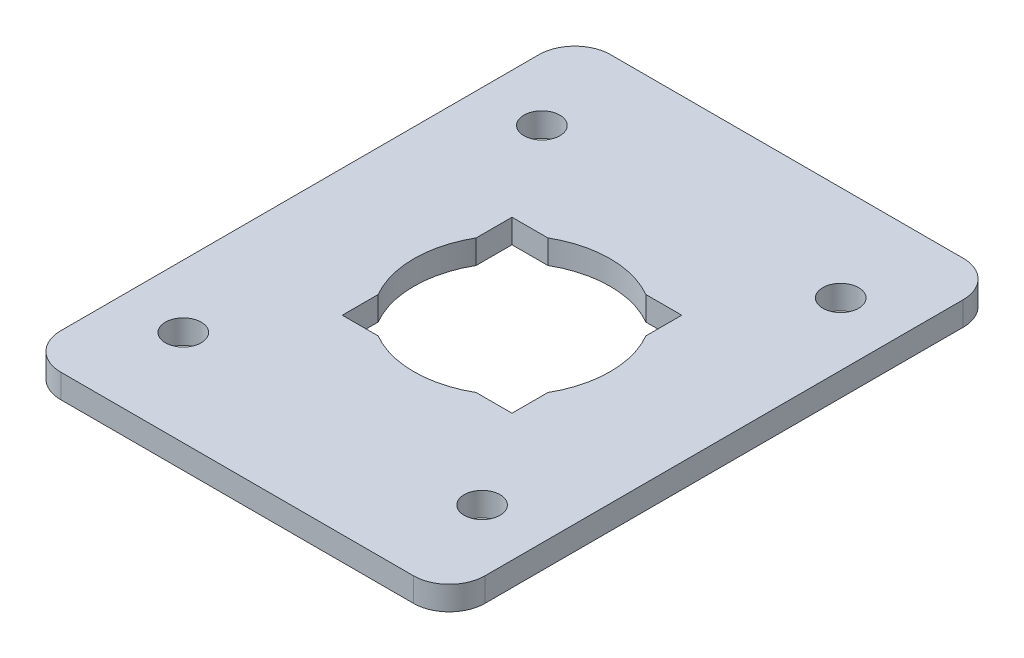
SolidWorks part; units mm, degrees
ref_plane "前视基准面" through (0, 0, 0) normal (0, 0, 1) x (1, 0, 0)
ref_plane "上视基准面" through (0, 0, 0) normal (0, 1, 0) x (1, 0, 0)
ref_plane "右视基准面" through (0, 0, 0) normal (1, 0, 0) x (0, 0, -1)
sketch "草图1" plane through (0, 0, 0) normal (0, 1, 0) x (1, 0, 0)
  line L4 (-6.2377, 3.1476) -> (-6.2377, 0.15)
  line L6 (-16.8877, -15.75) -> (18.6123, -15.75)
  line L7 (-16.8877, -15.75) -> (-16.8877, 30.25)
  line L8 (18.6123, -15.75) -> (18.6123, 30.25)
  line L9 (-16.8877, 30.25) -> (18.6123, 30.25)
  line L10 (-16.8877, -15.75) -> (18.6123, 30.25) construction
  line L11 (18.6123, -15.75) -> (-16.8877, 30.25) construction
  line L12 (-6.2377, 14.35) -> (-3.2402, 14.35)
  line L13 (-6.2377, 14.35) -> (-6.2377, 11.3524)
  line L14 (-6.2377, 0.15) -> (-3.2402, 0.15)
  line L15 (7.9623, 14.35) -> (7.9623, 11.3524)
  line L16 (-6.2377, 14.35) -> (7.9623, 0.15) construction
  line L17 (-6.2377, 0.15) -> (7.9623, 14.35) construction
  line L18 (7.9623, 3.1476) -> (7.9623, 0.15)
  line L19 (4.9647, 0.15) -> (7.9623, 0.15)
  line L20 (4.9647, 14.35) -> (7.9623, 14.35)
  arc A2 (7.9623, 3.1476) -> (7.9623, 11.3524) centre (0.8623, 7.25) ccw
  arc A3 (-3.2402, 0.15) -> (4.9647, 0.15) centre (0.8623, 7.25) ccw
  arc A4 (-6.2377, 11.3524) -> (-6.2377, 3.1476) centre (0.8623, 7.25) ccw
  arc A5 (4.9647, 14.35) -> (-3.2402, 14.35) centre (0.8623, 7.25) ccw
  point P0 (0.8623, 7.25)
  point P1 (0, 0)
  point P2 (0.8623, 7.25)
  dimension "D1" = 14.2
  dimension "D5" = 16.4
  dimension "D2" = 46
  dimension "D3" = 35.5
  dimension "D4" = 14.2
extrude "凸台-拉伸1" add sketch "草图1" along normal blind 2
fillet "圆角2" radius 3 4 edges at (18.6123, 1, 15.75) (-16.8877, 1, 15.75) (-16.8877, 1, -30.25) (18.6123, 1, -30.25)
sketch "草图2" plane through (0, 2, 0) normal (0, 1, 0) x (1, 0, 0)
  line L0 (10, -23.1319) -> (10, 23.1319)
  line L1 (10, -23.1319) -> (-10, -23.1319)
  line L2 (10, 23.1319) -> (-10, 23.1319)
  line L3 (-10, -23.1319) -> (-10, 23.1319)
  line L4 (10, -23.1319) -> (-10, 23.1319) construction
  line L5 (10, 23.1319) -> (-10, -23.1319) construction
  line L6 (12.5, -6.75) -> (12.5, 6.75)
  line L7 (-13.8877, -15.75) -> (15.6123, -15.75) construction
  line L8 (12.5, -6.75) -> (-12.5, -6.75)
  line L9 (12.5, 6.75) -> (-12.5, 6.75)
  line L10 (-12.5, -6.75) -> (-12.5, 6.75)
  line L11 (12.5, -6.75) -> (-12.5, 6.75) construction
  line L12 (12.5, 6.75) -> (-12.5, -6.75) construction
  circle A2 centre (-12.5, -6.75) radius 1.5
  circle A3 centre (-12.5, 6.75) radius 1.5
  circle A4 centre (12.5, 6.75) radius 1.5
  circle A5 centre (12.5, -6.75) radius 1.5
  point P1 (0, 0)
  point P2 (0, 0)
  dimension "D2" = 2.5
  dimension "D3" = 9
  dimension "D1" = 20
sketch "草图3" plane through (0, 0, 0) normal (0, -1, 0) x (1, 0, 0)
  line L0 (-16.8877, -7.25) -> (26.7138, -7.25) construction
  line L1 (-16.8877, -27.25) -> (-16.8877, 12.75) construction
  line L2 (0.8623, -30.25) -> (0.8623, 19.076) construction
  line L4 (15.6123, -30.25) -> (-13.8877, -30.25) construction
  circle A0 centre (-11.6377, 7.75) radius 1.5
  circle A4 centre (-11.6377, -22.25) radius 1.5
  circle A5 centre (13.3623, -22.25) radius 1.5
  circle A6 centre (13.3623, 7.75) radius 1.5
  dimension "D1" = 25
  dimension "D2" = 30
extrude "切除-拉伸1" cut sketch "草图3" against normal blind 10
